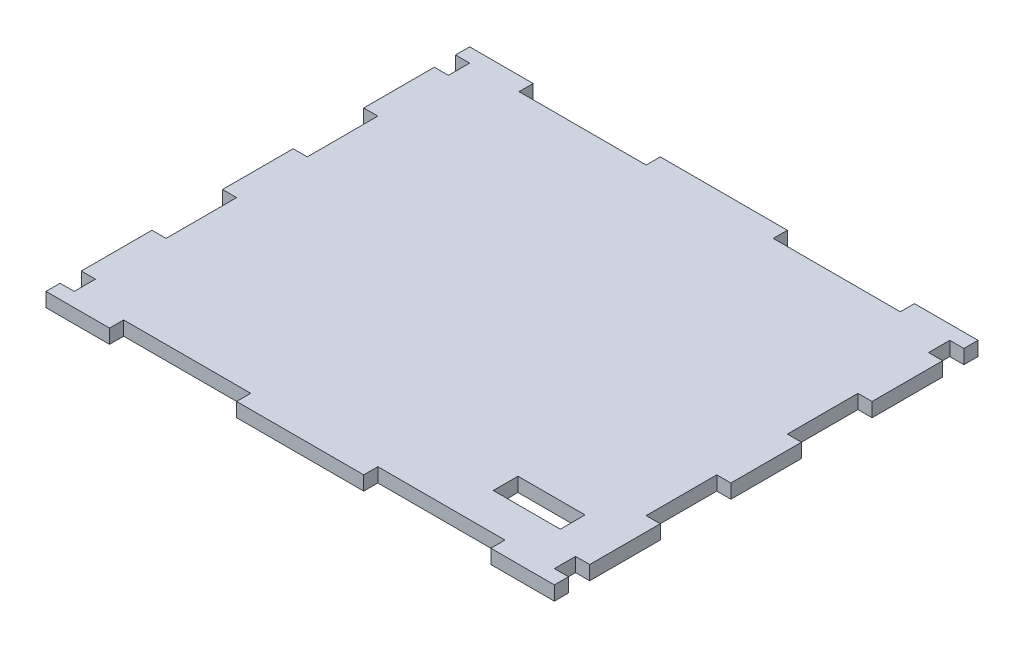
SolidWorks part; units mm, degrees
ref_plane "Front Plane" through (0, 0, 0) normal (0, 0, 1) x (1, 0, 0)
ref_plane "Top Plane" through (0, 0, 0) normal (0, 1, 0) x (1, 0, 0)
ref_plane "Right Plane" through (0, 0, 0) normal (1, 0, 0) x (0, 0, -1)
sketch "Sketch1" plane through (0, 0, 0) normal (0, 1, 0) x (1, 0, 0)
  line L0 (-114.3, 119.3252) -> (-85.725, 119.3252) construction
  line L1 (114.3, 95.25) -> (85.725, 95.25)
  line L2 (114.3, 95.25) -> (114.3, 88.9)
  line L3 (114.3, -95.25) -> (85.725, -95.25)
  line L4 (-114.3, 95.25) -> (-114.3, 88.9)
  line L5 (114.3, 95.25) -> (-114.3, -95.25) construction
  line L6 (114.3, -95.25) -> (-114.3, 95.25) construction
  line L7 (-85.725, 95.25) -> (-85.725, 88.9)
  line L8 (-28.575, 95.25) -> (-28.575, 88.9)
  line L9 (28.575, 95.25) -> (28.575, 88.9)
  line L10 (85.725, 95.25) -> (85.725, 88.9)
  line L11 (-114.3, 88.9) -> (-107.95, 88.9)
  line L12 (-85.725, 95.25) -> (-114.3, 95.25)
  line L13 (28.575, 88.9) -> (85.725, 88.9)
  line L14 (28.575, 95.25) -> (-28.575, 95.25)
  line L15 (0, -29.7904) -> (0, 27.6649) construction
  line L16 (123.6722, 92.075) -> (123.6722, 79.375) construction
  line L17 (114.3, 79.375) -> (107.95, 79.375)
  line L18 (107.95, 88.9) -> (107.95, 79.375)
  line L19 (114.3, 47.625) -> (107.95, 47.625)
  line L20 (114.3, 15.875) -> (107.95, 15.875)
  line L21 (114.3, -15.875) -> (107.95, -15.875)
  line L22 (114.3, -47.625) -> (107.95, -47.625)
  line L23 (114.3, -79.375) -> (107.95, -79.375)
  line L24 (133.2506, -95.25) -> (133.2506, -88.9) construction
  line L25 (114.3, -88.9) -> (107.95, -88.9)
  line L26 (114.3, -88.9) -> (114.3, -95.25)
  line L27 (107.95, -79.375) -> (107.95, -88.9)
  line L28 (114.3, -47.625) -> (114.3, -79.375)
  line L29 (107.95, -15.875) -> (107.95, -47.625)
  line L30 (114.3, 15.875) -> (114.3, -15.875)
  line L31 (107.95, 47.625) -> (107.95, 15.875)
  line L32 (114.3, 79.375) -> (114.3, 47.625)
  line L33 (107.95, 88.9) -> (114.3, 88.9)
  line L34 (-15.3754, 0) -> (16.7674, 0) construction
  line L35 (-107.95, 88.9) -> (-107.95, 79.375)
  line L36 (-114.3, 79.375) -> (-107.95, 79.375)
  line L37 (-114.3, 47.625) -> (-107.95, 47.625)
  line L38 (-107.95, 47.625) -> (-107.95, 15.875)
  line L39 (-114.3, 15.875) -> (-107.95, 15.875)
  line L40 (-114.3, -15.875) -> (-107.95, -15.875)
  line L41 (-107.95, -15.875) -> (-107.95, -47.625)
  line L42 (-114.3, -47.625) -> (-107.95, -47.625)
  line L43 (-114.3, -79.375) -> (-107.95, -79.375)
  line L44 (-107.95, -79.375) -> (-107.95, -88.9)
  line L45 (-114.3, -88.9) -> (-107.95, -88.9)
  line L46 (-114.3, -47.625) -> (-114.3, -79.375)
  line L47 (-114.3, -88.9) -> (-114.3, -95.25)
  line L48 (-114.3, 15.875) -> (-114.3, -15.875)
  line L49 (-114.3, 79.375) -> (-114.3, 47.625)
  line L50 (-85.725, 88.9) -> (-28.575, 88.9)
  line L51 (85.725, -95.25) -> (85.725, -88.9)
  line L52 (28.575, -88.9) -> (85.725, -88.9)
  line L53 (28.575, -95.25) -> (28.575, -88.9)
  line L54 (-28.575, -95.25) -> (-28.575, -88.9)
  line L55 (-85.725, -88.9) -> (-28.575, -88.9)
  line L56 (-85.725, -95.25) -> (-85.725, -88.9)
  line L57 (-85.725, -95.25) -> (-114.3, -95.25)
  line L58 (28.575, -95.25) -> (-28.575, -95.25)
  point P0 (0, 0)
  dimension "D1" = 228.6
  dimension "D2" = 190.5
  dimension "D3" = 28.575
  dimension "D4" = 6.35
  dimension "D6" = 12.7
  dimension "D7" = 6.35
  dimension "D10" = 6.35
  dimension "D5" = 4
  dimension "D8" = 6
extrude "Boss-Extrude2" add sketch "Sketch1" along normal blind 6.35
sketch "Sketch3" plane through (0, 6.35, 0) normal (0, 1, 0) x (1, 0, 0)
  line L1 (93.9502, -72.2213) -> (63.7877, -72.2213)
  line L2 (-107.95, -88.9) -> (-107.95, 88.9)
  line L3 (93.9502, -72.2213) -> (93.9502, -61.1088)
  line L4 (-107.95, -88.9) -> (107.95, -88.9)
  line L5 (107.95, -88.9) -> (107.95, 88.9)
  line L6 (93.9502, -61.1088) -> (63.7877, -61.1088)
  line L7 (63.7877, -72.2213) -> (63.7877, -61.1088)
  line L8 (107.95, 88.9) -> (-107.95, 88.9)
  dimension "D1" = 30.1625
  dimension "D2" = 11.1125
extrude "Cut-Extrude1" cut sketch "Sketch3" against normal blind 6.35 contours L7 L1 L3 L6
